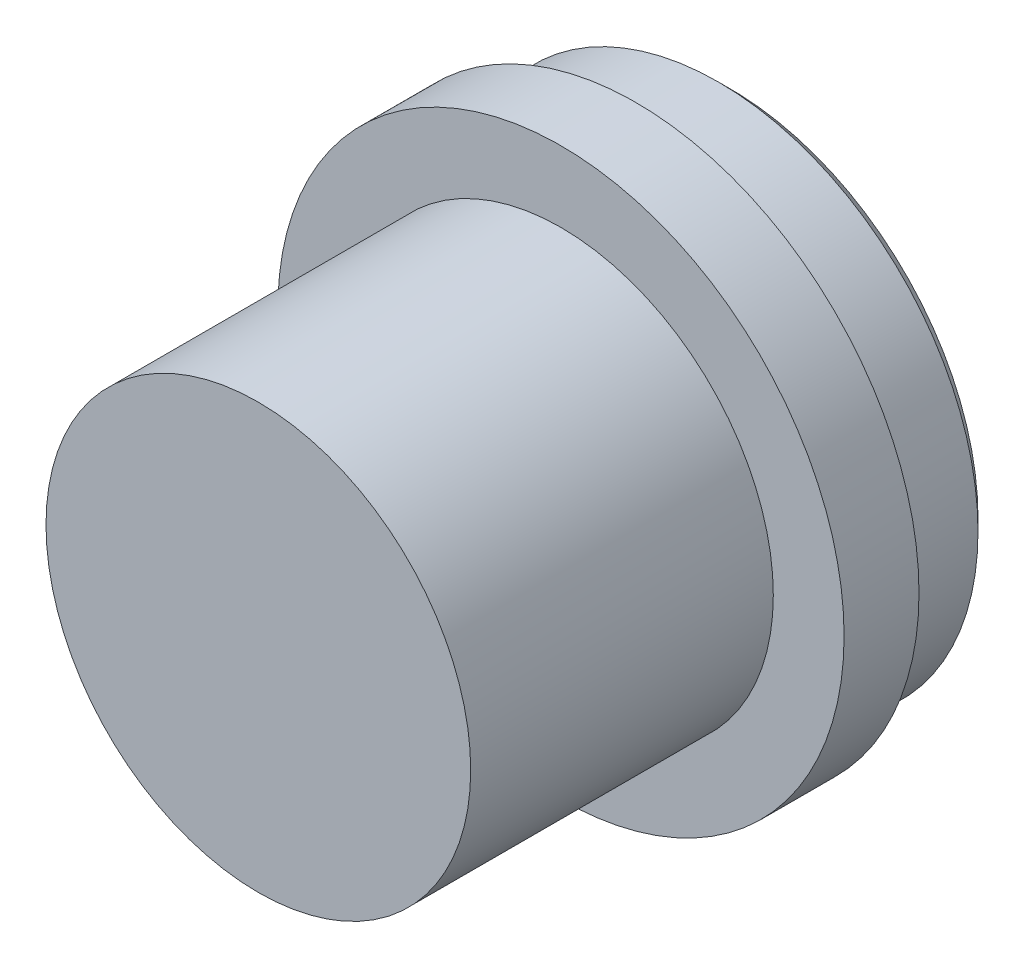
SolidWorks part; units mm, degrees
material "ABS"
ref_plane "Ground_Plane" through (0, 0, 0) normal (0, 0, 1) x (1, 0, 0)
ref_plane "VehicleCentre_Plane" through (0, 0, 0) normal (0, 1, 0) x (1, 0, 0)
ref_plane "FrontAxle_Plane" through (0, 0, 0) normal (1, 0, 0) x (0, 0, -1)
sketch "Sketch1" plane through (0, 0, 0) normal (0, 1, 0) x (1, 0, 0)
  line L0 (9, -20) -> (0, -20)
  line L1 (0, -20) -> (0, 0)
  line L2 (0, 0) -> (11, 0)
  line L3 (11, 0) -> (11, -4)
  line L4 (11, -4) -> (12, -4)
  line L5 (12, -4) -> (12, -7.175)
  line L6 (12, -7.175) -> (9, -7.175)
  line L7 (9, -7.175) -> (9, -20)
  point P2 (0, 0)
  dimension "D1" = 4
  dimension "D2" = 9
  dimension "D3" = 12
  dimension "D4" = 11
  dimension "D5" = 3.175
  dimension "D6" = 20
revolve "Revolve1" add sketch "Sketch1" angle 360 about L1
chamfer "Chamfer1" distance 0.5 angle 45 1 edges at (11, 0, 0)
